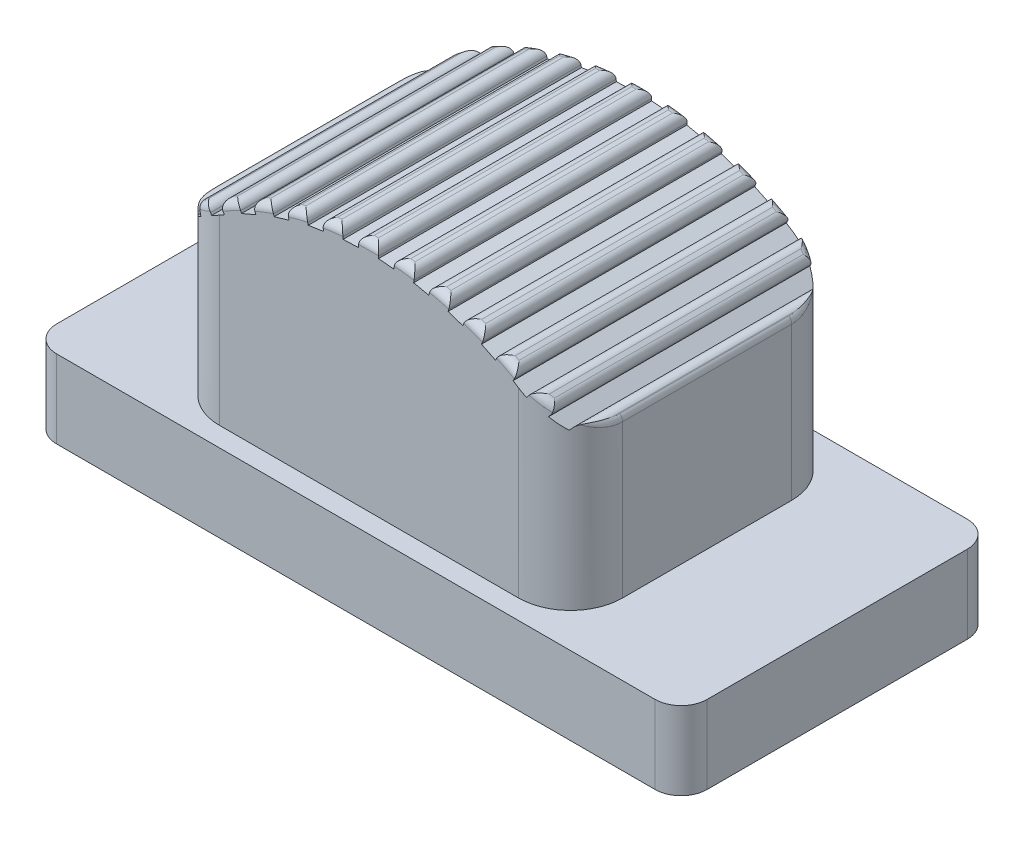
SolidWorks part; units mm, degrees
ref_plane "Front Plane" through (0, 0, 0) normal (0, 0, 1) x (1, 0, 0)
ref_plane "Top Plane" through (0, 0, 0) normal (0, 1, 0) x (1, 0, 0)
ref_plane "Right Plane" through (0, 0, 0) normal (1, 0, 0) x (0, 0, -1)
sketch "Sketch1" plane through (0, 0, 0) normal (0, 1, 0) x (1, 0, 0)
  line L1 (-12.5, -6) -> (12.5, -6)
  line L2 (-12.5, -6) -> (-12.5, 6)
  line L3 (-12.5, 6) -> (12.5, 6)
  line L4 (12.5, -6) -> (12.5, 6)
  line L5 (-12.5, -6) -> (12.5, 6) construction
  line L6 (-12.5, 6) -> (12.5, -6) construction
  point P0 (0, 0)
  dimension "D1" = 12
  dimension "D2" = 25
extrude "Boss-Extrude1" add sketch "Sketch1" along normal blind 3
sketch "Sketch2" plane through (0, 3, 0) normal (0, 1, 0) x (1, 0, 0)
  line L0 (-12.5, 2.5) -> (12.5, 2.5) construction
  line L1 (10, -5.4) -> (-10, -5.4) construction
  line L2 (10, -5.4) -> (10, 5.4) construction
  line L3 (10, 5.4) -> (-10, 5.4) construction
  line L4 (-10, -5.4) -> (-10, 5.4) construction
  line L5 (10, -5.4) -> (-10, 5.4) construction
  line L6 (10, 5.4) -> (-10, -5.4) construction
  line L7 (-12.5, 6) -> (-12.5, -6) construction
  line L8 (12.5, -6) -> (12.5, 6) construction
  line L9 (-12.5, -2.5) -> (12.5, -2.5) construction
  line L10 (12.5, 6) -> (-12.5, 6) construction
  line L11 (-12.5, -6) -> (12.5, -6) construction
  line L13 (-2.3, 2.5) -> (4, 2.5)
  line L14 (-2.3, 2.5) -> (-2.3, -2.5)
  line L15 (-2.3, -2.5) -> (4, -2.5)
  line L16 (4, 2.5) -> (4, -2.5)
  point P0 (0, 0)
  dimension "D1" = 20
  dimension "D2" = 10.8
  dimension "D3" = 3.5
  dimension "D4" = 3.5
  dimension "D5" = 6.3
  dimension "D6" = 6
extrude "Cut-Extrude1" cut sketch "Sketch2" against normal through all
sketch "Sketch4" plane through (0, 3, 0) normal (0, 1, 0) x (1, 0, 0)
  line L1 (-2.3, 2.5) -> (4, -2.5) construction
  line L2 (4, 2.5) -> (0.85, 0) construction
  line L4 (-5.8, -5.25) -> (7.5, -5.25)
  line L5 (-2.3, -2.5) -> (4, -2.5)
  line L6 (-2.3, 2.5) -> (-2.3, -2.5)
  line L7 (4, 2.5) -> (-2.3, 2.5)
  line L8 (4, -2.5) -> (4, 2.5)
  line L9 (-2.3, -2.5) -> (4, -2.5)
  line L10 (-2.3, 2.5) -> (-2.3, -2.5)
  line L11 (4, 2.5) -> (-2.3, 2.5)
  line L12 (4, -2.5) -> (4, 2.5)
  line L13 (-5.8, -5.25) -> (-5.8, 5.25) construction
  line L14 (-5.8, 5.25) -> (7.5, 5.25)
  line L15 (7.5, -5.25) -> (7.5, 5.25)
  line L16 (-5.8, -5.25) -> (7.5, 5.25) construction
  line L17 (-5.8, 5.25) -> (7.5, -5.25) construction
  line L18 (-5.8, 5.25) -> (-8, 5.25)
  line L19 (-5.8, 5.25) -> (-5.8, -5.25)
  line L20 (-5.8, -5.25) -> (-8, -5.25)
  line L21 (-8, 5.25) -> (-8, -5.25)
  line M13 (4, -2.5) -> (-2.3, -2.5)
  line M14 (-2.3, -2.5) -> (-2.3, 2.5)
  line M15 (-2.3, 2.5) -> (4, 2.5)
  line M16 (4, 2.5) -> (4, -2.5)
  dimension "D2" = 10.5
  dimension "D3" = 3.5
  dimension "D4" = 12
  dimension "D1" = 0
extrude "Boss-Extrude2" add sketch "Sketch4" along normal offset from surface (6 mm away) 9 contours L18 L21 L20 L19 | L14 L19 L4 L15 M16 M13 M14 M15 up to face at (0.85, 0, 0)
sketch "Sketch5" plane through (0, 0, 5.25) normal (0, 0, 1) x (1, 0, 0)
  line L0 (-8, 9) -> (7.5, 9) construction
  line L1 (-8, 9) -> (7.5, 9)
  line L2 (-0.25, 9) -> (-0.25, 12) construction
  arc A0 (-8, 9) -> (7.5, 9) centre (-0.25, 0.4896) cw
  dimension "D1" = 3
extrude "Boss-Extrude3" add sketch "Sketch5" against normal up to surface (10.5 mm away) up to face at (-0.25, 6, -5.25)
sketch "Sketch6" plane through (0, 0, -5.25) normal (0, 0, -1) x (-1, 0, 0)
  line L0 (-7.1468, 9.3087) -> (-6.8871, 8.9992)
  line L1 (-6.8871, 8.9992) -> (-6.4274, 9.3847)
  line L2 (-6.4274, 9.3847) -> (-6.6602, 9.6949)
  line L3 (-6.6602, 9.6949) -> (-3.6026, 11.9903) construction
  line L4 (-7.1468, 9.3087) -> (-9.0588, 7.7051) construction
  arc A0 (8, 9) -> (-7.5, 9) centre (0.25, 0.4896) ccw construction
  arc A1 (8, 9) -> (-7.5, 9) centre (0.25, 0.4896) ccw
  point P5 (-6.3466, 8.3547)
  point P10 (-6.0841, 9.3087)
  point P11 (-6.6573, 9.192)
  arc M7 (8, 9) -> (-7.5, 9) centre (0.25, 0.4896) ccw
  dimension "D1" = 0.4692
  dimension "D2" = 0.4
  dimension "D3" = 0.6
extrude "Cut-Extrude2" cut sketch "Sketch6" against normal through all contours L1 L2 L0 M7
pattern_circular "CirPattern1" count 12 over 77 about axis through (-0.25, 0.4896, 0) along (0, 0, 1) of "Cut-Extrude2"
fillet "Fillet1" radius 2 4 edges at (7.5, 6, 5.25) (-8, 6, 5.25) (7.5, 6, -5.25) (-8, 6, -5.25)
fillet "Fillet2" radius 1 4 edges at (-12.5, 1.5, 6) (12.5, 1.5, 6) (12.5, 1.5, -6) (-12.5, 1.5, -6)
fillet "Fillet3" radius 0.3 52 edges at (-7.9036, 9.0868, -3.8633) (-7.6649, 9.2935, 0) (-7.9204, 9.0718, 3.8087) (-8, 9, 0) (-6.5367, 10.1315, 0) (-7.1792, 9.6806, 0) (-5.6643, 10.6471, 5.25) (-5.6643, 10.6471, -5.25) (-6.0075, 10.4566, 0) (-5.3148, 10.8258, 0) (-4.386, 11.2312, 5.25) (-4.386, 11.2312, -5.25) (-4.7499, 11.084, 0) (-4.0174, 11.366, 0) (-1.6646, 11.9127, 5.25) (-1.6646, 11.9127, -5.25) (-2.0532, 11.8579, 0) (-1.2743, 11.9543, 0) (-3.0461, 11.6552, 5.25) (-3.0461, 11.6552, -5.25) (-3.4252, 11.5534, 0) (-2.6638, 11.7441, 0) (-0.2619, 12, 5.25) (-0.2619, 12, -5.25) (-0.6543, 11.9929, 0) (0.1306, 11.9937, 0) (1.141, 11.9156, 5.25) (1.141, 11.9156, -5.25) (0.7506, 11.9564, 0) (1.5297, 11.8616, 0) (7.4237, 9.0688, -3.7971) (7.5, 9, 0) (7.3951, 9.0944, 3.8893) (7.1468, 9.3087, 0) (6.6602, 9.6949, 0) (6.0168, 10.1444, 0) (5.1433, 10.6582, 5.25) (5.1433, 10.6582, -5.25) (4.7935, 10.8362, 0) (5.4869, 10.4685, 0) (3.8639, 11.2397, 5.25) (3.8639, 11.2397, -5.25) (3.495, 11.3737, 0) (4.228, 11.0932, 0) (2.5231, 11.661, 5.25) (2.5231, 11.661, -5.25) (2.1406, 11.749, 0) (2.9024, 11.5599, 0)
fillet "Fillet4" radius 0.6 4 edges at (-2.3, 0, 0) (0.85, 0, -2.5) (4, 0, 0) (0.85, 0, 2.5)
